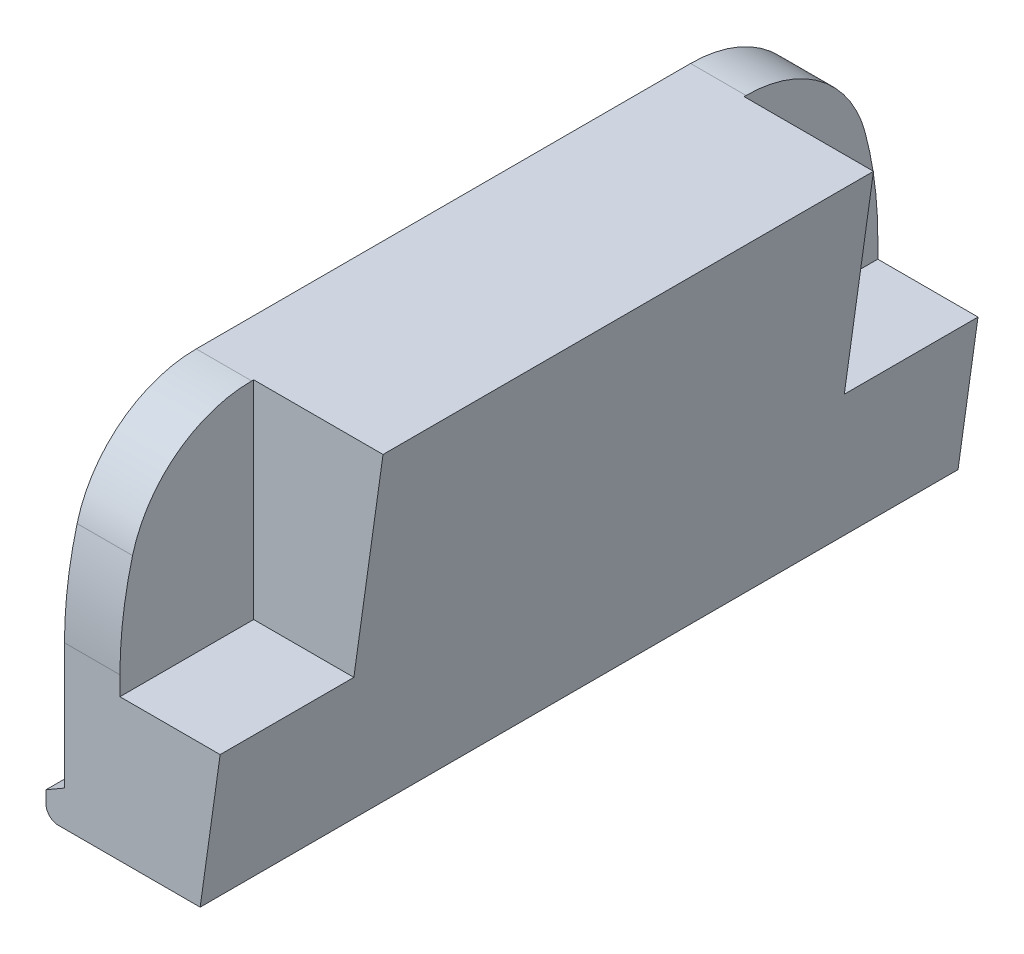
SolidWorks part; units mm, degrees
ref_plane "Front Plane" through (0, 0, 0) normal (0, 0, 1) x (1, 0, 0)
ref_plane "Top Plane" through (0, 0, 0) normal (0, 1, 0) x (1, 0, 0)
ref_plane "Right Plane" through (0, 0, 0) normal (1, 0, 0) x (0, 0, -1)
sketch "Sketch1" plane through (0, 0, 0) normal (0, 0, 1) x (1, 0, 0)
  line L0 (0, 0) -> (0.3, 0.1732)
  line L1 (0.3, 6.1075) -> (0.3, 1.7816)
  line L2 (0.3, 6.1075) -> (3.3, 6.1075)
  line L3 (3.3, 6.1075) -> (3.3, 0.6468)
  line L4 (0.3, 1.7816) -> (0.3, 0.1732)
  line L5 (0.3, 0.9774) -> (0.15, 0.0866) construction
  line L6 (2.3013, 0.5964) -> (0.3, 0.1732) construction
  line L7 (1.3155, -0.3379) -> (0.3, 0.1732) construction
  line L8 (1.3155, -0.3379) -> (3.3, 0.6468) construction
  line L9 (3.3, 0.6468) -> (3.3, -0.4)
  line L10 (3.3, -0.4) -> (0.2, -0.4)
  line L11 (0, 0) -> (0, -0.2)
  arc A0 (3.3, 0.6468) -> (2.3013, 0.5964) centre (8.5649, -113.5554) ccw construction
  arc A1 (0.2, -0.4) -> (0, -0.2) centre (0.2, -0.2) cw
  point P9 (0.3, 1.7816)
  point P10 (0, -3.0581)
  point P17 (0, -0.4)
  dimension "D1" = 0.3464
  dimension "D2" = 114.3235
  dimension "D3" = 5.9342
  dimension "D6" = 1
  dimension "D12" = 0.2
  dimension "D4" = 3
  dimension "D5" = 5.4606
  dimension "D7" = 1.6084
  dimension "D8" = 0.9033
  dimension "D9" = 1.1369
  dimension "D10" = 2.2154
  dimension "D11" = 0.4
extrude "Boss-Extrude1" add sketch "Sketch1" along normal blind 12.3
sketch "Sketch2" plane through (0, 6.1075, 0) normal (0, 1, 0) x (1, 0, 0)
  line L0 (3.3, -6.15) -> (0.3, -6.15) construction
  line L1 (3.3, 0) -> (1.2, 0)
  line L2 (3.3, 0) -> (3.3, -2.17)
  line L3 (3.3, -2.17) -> (1.2, -2.17)
  line L4 (1.2, 0) -> (1.2, -2.17)
  line L5 (3.3, -12.3) -> (3.3, 0) construction
  line L6 (0.3, -12.3) -> (0.3, 0) construction
  line L7 (3.3, -10.13) -> (1.2, -10.13)
  line L8 (3.3, -12.3) -> (3.3, -10.13)
  line L9 (3.3, -12.3) -> (1.2, -12.3)
  line L10 (1.2, -12.3) -> (1.2, -10.13)
  dimension "D1" = 2.17
  dimension "D2" = 2.1
extrude "Cut-Extrude1" cut sketch "Sketch2" against normal blind 4.2
sketch "Sketch4" plane through (0.3, 0, 0) normal (-1, 0, 0) x (0, 0, 1)
  line L0 (12.3, 0.1732) -> (12.3, 2.2159) construction
  line L1 (12.3, 6.1075) -> (12.3, 0.1732) construction
  line L2 (1.8884, 6.1075) -> (10.4116, 6.1075) construction
  line L3 (12.3, 6.1075) -> (0, 6.1075) construction
  line L4 (6.15, 6.1075) -> (6.15, 0.1732) construction
  line L5 (12.3, 0.1732) -> (0, 0.1732) construction
  line L6 (11.2391, 5.669) -> (10.4116, 6.1075) construction
  line L7 (10.4116, 6.1075) -> (12.3, 6.1075)
  line L8 (12.3, 6.1075) -> (12.3, 2.2159)
  line L9 (1.8884, 6.1075) -> (0, 6.1075)
  line L10 (0, 6.1075) -> (0, 2.2159)
  arc A0 (12.3, 2.2159) -> (11.2391, 5.669) centre (6.1496, 2.2159) ccw
  arc A1 (11.2391, 5.669) -> (10.4116, 6.1075) centre (10.4119, 5.1078) ccw
  arc A2 (1.0609, 5.669) -> (1.8884, 6.1075) centre (1.8881, 5.1078) cw
  arc A3 (0, 2.2159) -> (1.0609, 5.669) centre (6.1504, 2.2159) cw
  dimension "D1" = 8.5232
  dimension "D2" = 0.9365
  dimension "D3" = 3.6124
  dimension "D4" = 3.6665
extrude "Cut-Extrude3" cut sketch "Sketch4" against normal up to surface (0.9 mm away) up to face at (1.2, 4.0075, 11.215)
sketch "Sketch5" plane through (0.3, 0, 0) normal (-1, 0, 0) x (0, 0, 1)
  line L0 (6.15, 1.7816) -> (6.15, 0.1732) construction
  line L1 (4.65, 2.7816) -> (7.65, 2.7816)
  line L2 (4.65, 2.7816) -> (4.65, 1.7816)
  line L3 (4.65, 1.7816) -> (7.65, 1.7816)
  line L4 (7.65, 2.7816) -> (7.65, 1.7816)
  line L5 (12.3, 0.1732) -> (0, 0.1732) construction
  dimension "D1" = 1.6084
  dimension "D2" = 3
  dimension "D3" = 1
extrude "Boss-Extrude2" add sketch "Sketch5" along normal blind 0.55
sketch "Sketch6" plane through (0, 0, 7.65) normal (0, 0, 1) x (1, 0, 0)
  line L0 (0.3, 2.7816) -> (0.3, 4.3732)
  line L1 (0.3, 5.669) -> (0.3, 2.2159) construction
  line L2 (0.3, 4.3732) -> (-0.25, 2.7816)
  line L3 (-0.25, 2.7816) -> (0.3, 2.7816)
  dimension "D1" = 1.5916
extrude "Boss-Extrude3" add sketch "Sketch6" against normal up to surface (3 mm away) up to face at (0.025, 2.2816, 4.65)
sketch "Sketch7" plane through (0.3, 0, 0) normal (-1, 0, 0) x (0, 0, 1)
  line L1 (-0.5522, 6.1075) -> (12.4609, 6.1075)
  line L2 (-0.5522, 6.1075) -> (-0.5522, 5.2775)
  line L3 (-0.5522, 5.2775) -> (12.4609, 5.2775)
  line L4 (12.4609, 6.1075) -> (12.4609, 5.2775)
  line L5 (10.4119, 6.1075) -> (1.8881, 6.1075) construction
  dimension "D1" = 0.83
  dimension "D2" = 0
extrude "Cut-Extrude4" cut sketch "Sketch7" against normal through all
fillet "Fillet1" radius 2 2 edges at (0.75, 5.2775, 11.4839) (0.75, 5.2775, 0.8161)
ref_plane "Plane1" through (0, 0, 6.15) normal (0, 0, 1) x (1, 0, 0)
sketch "Sketch16" plane through (0, 0, 12.3) normal (0, 0, 1) x (1, 0, 0)
  line L0 (3.3, 5.2775) -> (3.3, -0.4)
  line L1 (3.3, -0.4) -> (2.5021, -0.4)
  line L2 (0.2, -0.4) -> (3.3, -0.4) construction
  line L3 (2.5021, -0.4) -> (3.3, 5.2775)
  dimension "D1" = 8
extrude "Cut-Extrude8" cut sketch "Sketch16" against normal through all
